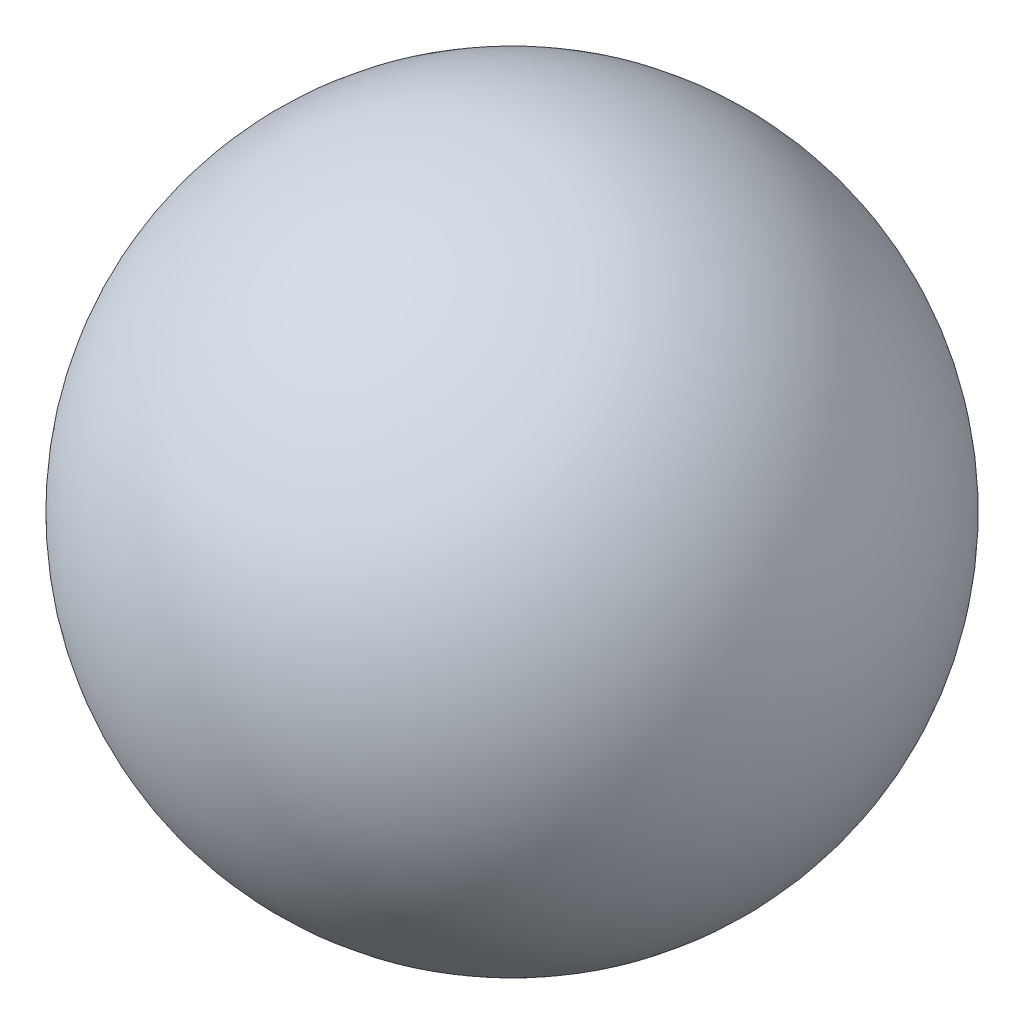
SolidWorks part; units mm, degrees
ref_plane "Plane1" through (0, 0, 0) normal (0, 0, 1) x (1, 0, 0)
ref_plane "Plane2" through (0, 0, 0) normal (0, 1, 0) x (1, 0, 0)
ref_plane "Plane3" through (0, 0, 0) normal (1, 0, 0) x (0, 0, -1)
other "Configuration Table"
sketch "Sketch1" plane through (0, 0, 0) normal (0, 0, 1) x (1, 0, 0)
  line L0 (0, 0) -> (0, 272.1834)
  line L1 (0, 113.2855) -> (0, -20.058) construction
  arc A0 (0, 272.1834) -> (0, 0) centre (0, 136.0917) cw
revolve "Base-Revolve" add sketch "Sketch1" angle 360 about L1
